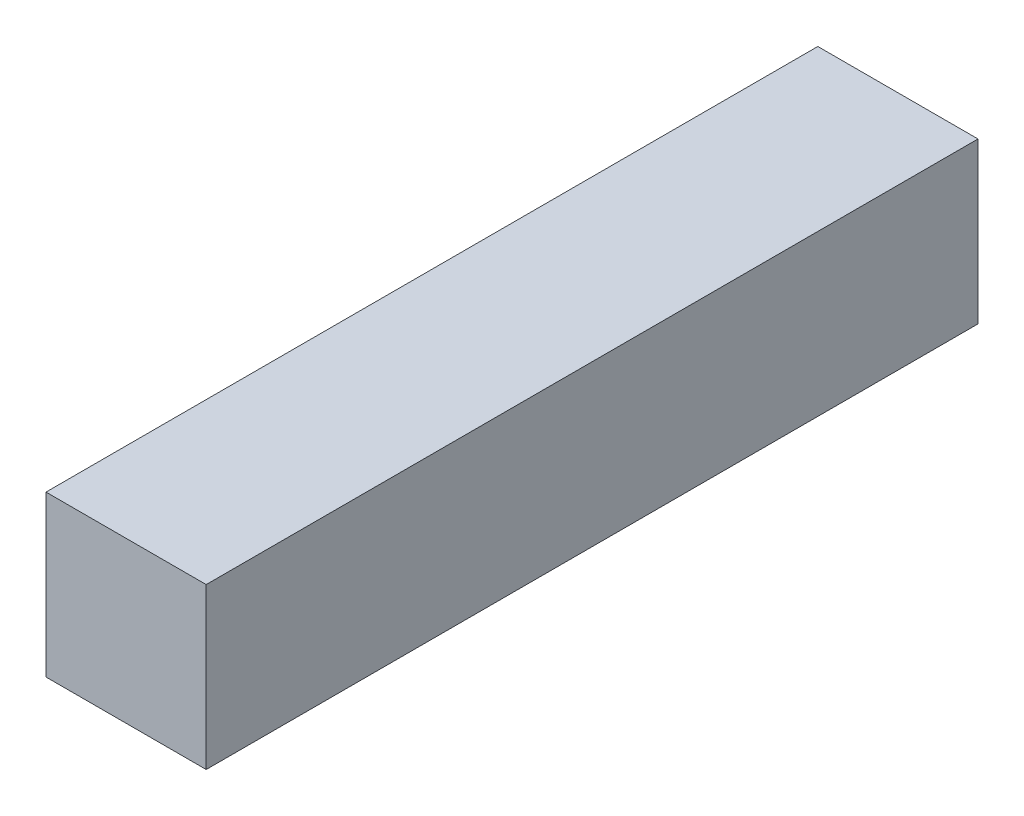
SolidWorks part; units mm, degrees
ref_plane "Front Plane" through (0, 0, 0) normal (0, 0, 1) x (1, 0, 0)
ref_plane "Top Plane" through (0, 0, 0) normal (0, 1, 0) x (1, 0, 0)
ref_plane "Right Plane" through (0, 0, 0) normal (1, 0, 0) x (0, 0, -1)
sketch "Sketch1" plane through (0, 0, 0) normal (0, 0, 1) x (1, 0, 0)
  line L1 (-11, 11) -> (11, 11)
  line L2 (-11, 11) -> (-11, -11)
  line L3 (-11, -11) -> (11, -11)
  line L4 (11, 11) -> (11, -11)
  line L5 (-11, 11) -> (11, -11) construction
  line L6 (-11, -11) -> (11, 11) construction
  point P0 (0, 0)
  dimension "D1" = 22
  dimension "D2" = 22
extrude "Boss-Extrude1" add sketch "Sketch1" along normal blind 106
